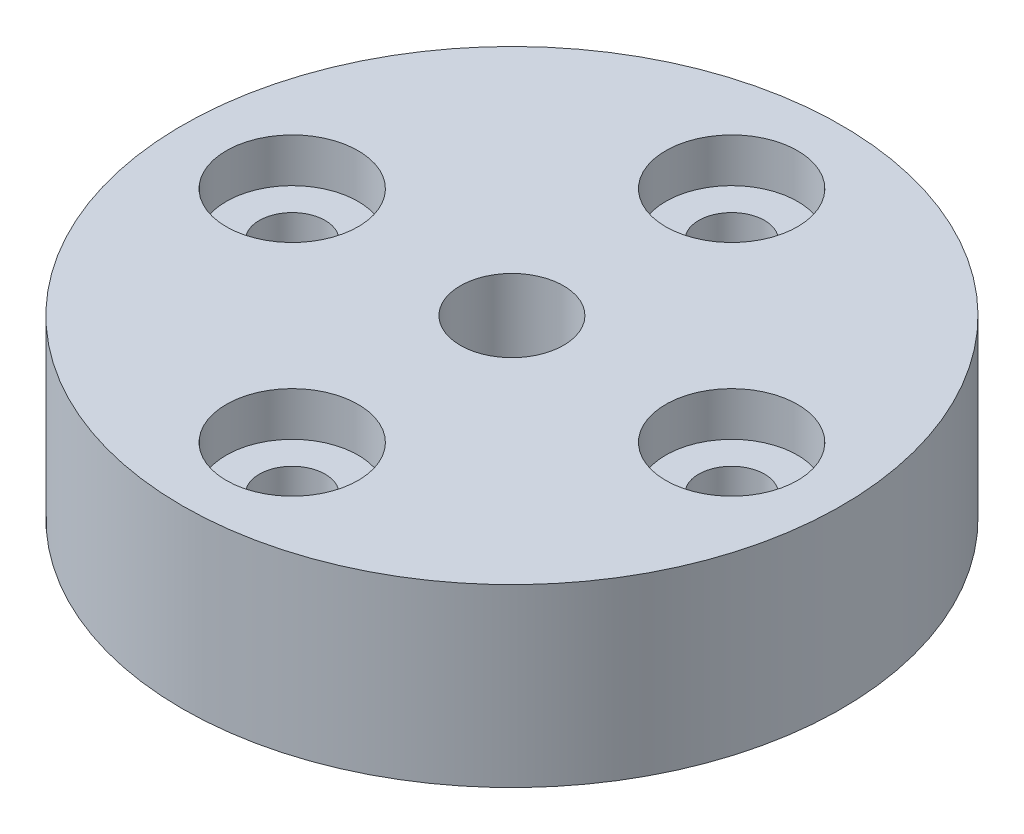
SolidWorks part; units mm, degrees
ref_plane "前视基准面" through (0, 0, 0) normal (0, 0, 1) x (1, 0, 0)
ref_plane "上视基准面" through (0, 0, 0) normal (0, 1, 0) x (1, 0, 0)
ref_plane "右视基准面" through (0, 0, 0) normal (1, 0, 0) x (0, 0, -1)
other "Configuration Table"
sketch "Sketch1" plane through (0, 0, 0) normal (0, 1, 0) x (1, 0, 0)
  circle A0 centre (0, 0) radius 15
  circle A1 centre (0, 0) radius 10
  circle A2 centre (0, 10) radius 1.5
  circle A3 centre (10, 0) radius 1.5
  circle A4 centre (0, -10) radius 1.5
  circle A5 centre (-10, 0) radius 1.5
  point P15 (0, 0)
  dimension "D1" = 30
  dimension "D2" = 20
  dimension "D3" = 3
  dimension "D4" = 4
extrude "Boss-Extrude1" add sketch "Sketch1" along normal blind 8 contours A0 A5 A1 A2 A3 A4 | A5 A1 A4 A3 A2
sketch "Sketch2" plane through (0, 8, 0) normal (0, 1, 0) x (1, 0, 0)
  circle A0 centre (0, 0) radius 2.35
  dimension "D1" = 4.7
extrude "Cut-Extrude1" cut sketch "Sketch2" against normal through all
sketch "Sketch3" plane through (0, 8, 0) normal (0, 1, 0) x (1, 0, 0)
  circle A0 centre (0, 10) radius 3
  circle A1 centre (10, 0) radius 3
  circle A2 centre (0, -10) radius 3
  circle A3 centre (-10, 0) radius 3
  point P12 (0, 0)
  circle M2 centre (-10, 0) radius 1.5
  circle M4 centre (10, 0) radius 1.5
  circle M5 centre (0, -10) radius 1.5
  dimension "D1" = 6
  dimension "D2" = 4
extrude "Cut-Extrude2" cut sketch "Sketch3" against normal blind 2 contours A3 M2 | A2 M5 | A1 M4 | A0
sketch "Sketch4" plane through (0, 0, 0) normal (0, -1, 0) x (1, 0, 0)
  circle A0 centre (0, 10) radius 3
  circle A1 centre (10, 0) radius 3
  circle A2 centre (0, -10) radius 3
  circle A3 centre (-10, 0) radius 3
  point P12 (0, 0)
  dimension "D1" = 6
  dimension "D2" = 4
extrude "Cut-Extrude3" cut sketch "Sketch4" against normal blind 2
